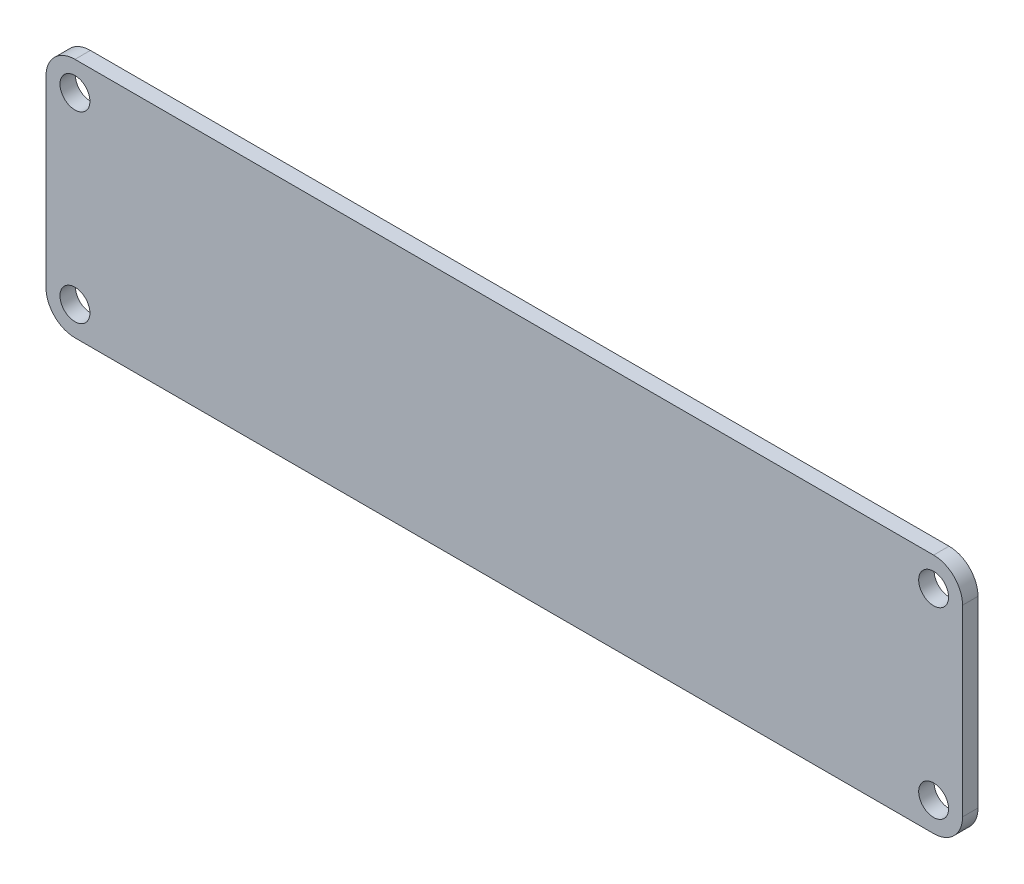
SolidWorks part; units mm, degrees
material "ABS"
ref_plane "Спереди" through (0, 0, 0) normal (0, 0, 1) x (1, 0, 0)
ref_plane "Сверху" through (0, 0, 0) normal (0, 1, 0) x (1, 0, 0)
ref_plane "Справа" through (0, 0, 0) normal (1, 0, 0) x (0, 0, -1)
sketch "Эскиз1" plane through (0, 0, 0) normal (0, 0, 1) x (1, 0, 0)
  line L1 (-44.5, 12.5) -> (44.5, 12.5)
  line L2 (-47.5, 9.5) -> (-47.5, -9.5)
  line L3 (-44.5, -12.5) -> (44.5, -12.5)
  line L4 (47.5, 9.5) -> (47.5, -9.5)
  line L5 (-47.5, 12.5) -> (47.5, -12.5) construction
  line L6 (-47.5, -12.5) -> (47.5, 12.5) construction
  arc A0 (44.5, -12.5) -> (47.5, -9.5) centre (44.5, -9.5) ccw
  arc A1 (44.5, 12.5) -> (47.5, 9.5) centre (44.5, 9.5) cw
  arc A2 (-47.5, -9.5) -> (-44.5, -12.5) centre (-44.5, -9.5) ccw
  arc A3 (-44.5, 12.5) -> (-47.5, 9.5) centre (-44.5, 9.5) ccw
  circle A4 centre (-44.5, 9.5) radius 1.55
  circle A5 centre (-44.5, -9.5) radius 1.55
  circle A6 centre (44.5, -9.5) radius 1.55
  circle A7 centre (44.5, 9.5) radius 1.55
  point P0 (0, 0)
  dimension "D3" = 3
  dimension "D4" = 3.1
  dimension "D1" = 25
  dimension "D2" = 95
extrude "Бобышка-Вытянуть1" add sketch "Эскиз1" along normal blind 1.6
